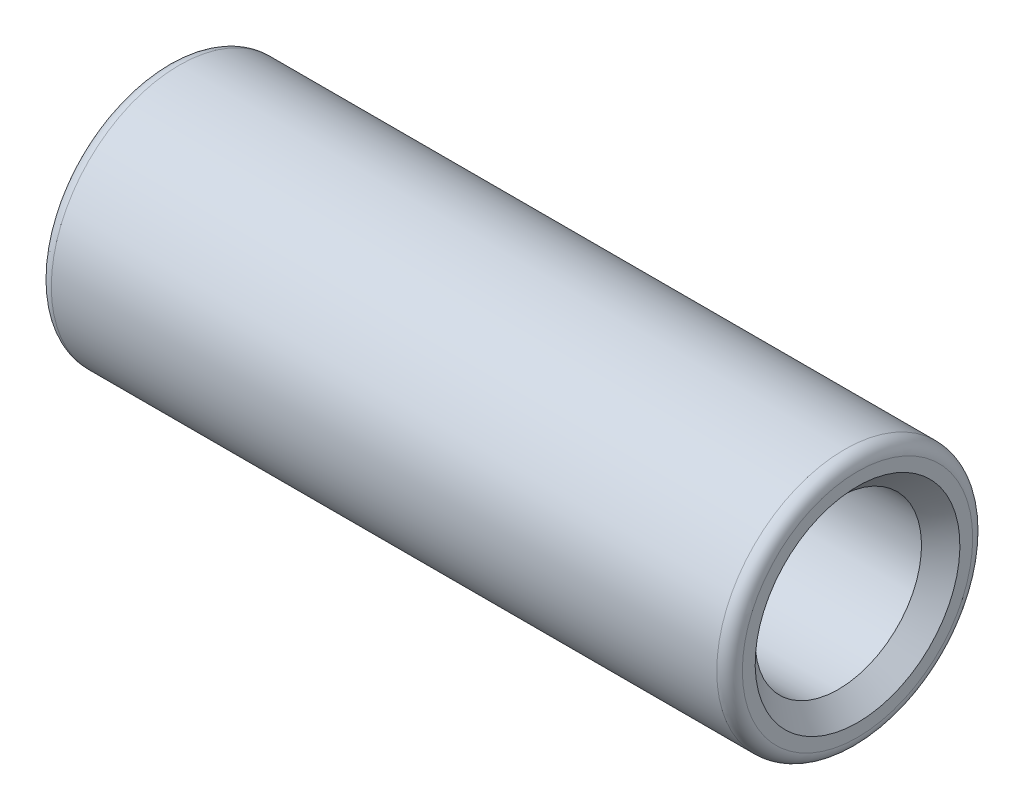
SolidWorks part; units mm, degrees
ref_plane "Front" through (0, 0, 0) normal (0, 0, 1) x (1, 0, 0)
ref_plane "Top" through (0, 0, 0) normal (0, 1, 0) x (1, 0, 0)
ref_plane "Right" through (0, 0, 0) normal (1, 0, 0) x (0, 0, -1)
sketch "Sketch1" plane through (0, 0, 0) normal (0, 0, 1) x (1, 0, 0)
  line L0 (0, 0) -> (36, 0) construction
  line L1 (25, 4.05) -> (0, 4.05)
  line L4 (54, 10) -> (54, 6.5)
  line L5 (54, 6.5) -> (30, 6.5)
  line L6 (30, 6.5) -> (30, 2.775)
  line L7 (30, 2.775) -> (36, 2.775)
  line L8 (36, 2.775) -> (36, 0)
  line L9 (36, 0) -> (25, 0)
  line L10 (25, 0) -> (25, 4.05)
  line L11 (54, 10) -> (0, 10)
  line L14 (0, 10) -> (0, 4.05)
  point P6 (0, 11.3103)
  point P14 (0, 0)
  dimension "D1" = 8.1
  dimension "D2" = 25
  dimension "D3" = 5.55
  dimension "D4" = 13
  dimension "D5" = 6
  dimension "D6" = 24
  dimension "D7" = 5
  dimension "D8" = 3.5
revolve "Revolve1" add sketch "Sketch1" angle 360 about L0
chamfer "Chamfer1" distance 1.5 angle 45 3 edges at (36, -2.775, 0) (54, -6.5, 0) (0, -4.05, 0)
fillet "Fillet1" radius 1 2 edges at (0, -10, 0) (54, -10, 0)
